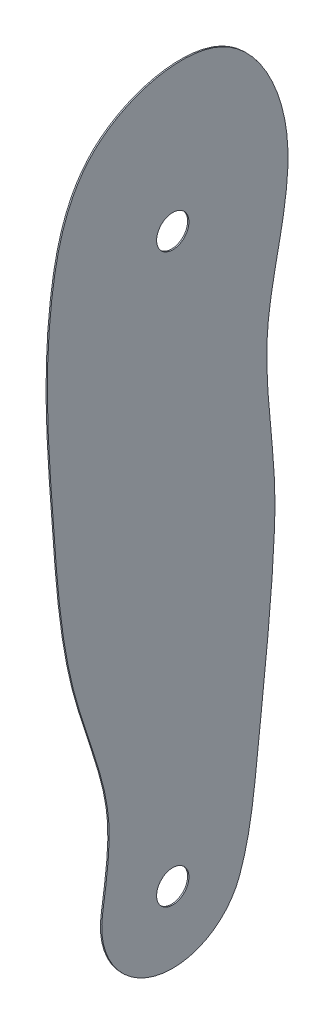
SolidWorks part; units mm, degrees
material "Teras S325"
ref_plane "Front Plane" through (0, 0, 0) normal (0, 0, 1) x (1, 0, 0)
ref_plane "Top Plane" through (0, 0, 0) normal (0, 1, 0) x (1, 0, 0)
ref_plane "Right Plane" through (0, 0, 0) normal (1, 0, 0) x (0, 0, -1)
sketch "Sketch3" plane through (0, 0, 0) normal (1, 0, 0) x (0, 0, -1)
  line L0 (0, 55) -> (0, -55) construction
  line L1 (0, 0) -> (0, -439.0843) construction
  circle A0 centre (0, 0) radius 12.5
  circle A1 centre (0, -439.0843) radius 12.5
  arc A2 (-54.2646, -430.1205) -> (51.7925, -457.5922) centre (0, -439.0843) ccw
  spline S0 degree 3 poles (51.7925, -457.5922) (60.1607, -434.1744) (67.4886, -363.1307) (77.2117, -282.1015) (80.6409, -188.942) (61.2272, -97.6292) (106.8577, 11.1934) (47.1237, 128.829) (-73.2115, 98.5223) (-102.6355, -20.0158) (-92.6576, -140.9582) (-84.605, -265.6649) (-43.7726, -358.4091) (-50.6651, -405.5185) (-54.2646, -430.1205) knots 0 0 0 0 0.060565 0.171945 0.195188 0.292997 0.398657 0.47911 0.561346 0.633895 0.762588 0.868561 0.947252 1 1 1 1
  dimension "D1" = 25
  dimension "D2" = 25
  dimension "D3" = 110
extrude "Extrude1" add sketch "Sketch3" along normal mid plane 1
